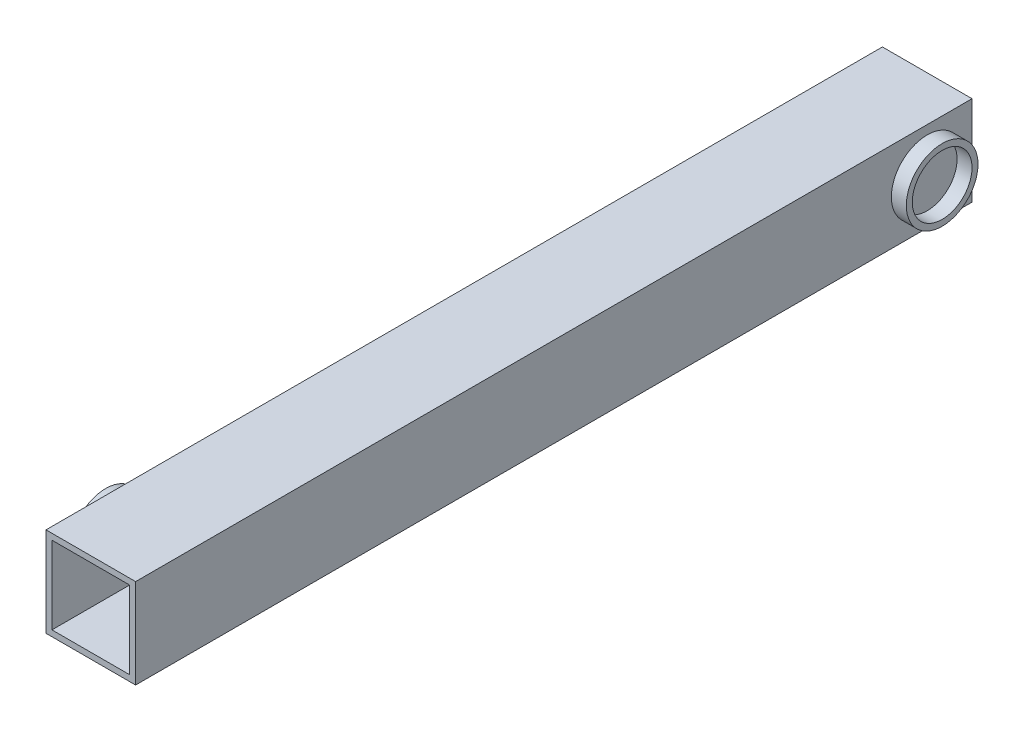
SolidWorks part; units mm, degrees
ref_plane "Front Plane" through (0, 0, 0) normal (0, 0, 1) x (1, 0, 0)
ref_plane "Top Plane" through (0, 0, 0) normal (0, 1, 0) x (1, 0, 0)
ref_plane "Right Plane" through (0, 0, 0) normal (1, 0, 0) x (0, 0, -1)
sketch "Sketch1" plane through (0, 0, 0) normal (0, 0, 1) x (1, 0, 0)
  line L0 (-13, 13) -> (-13, -13)
  line L1 (-15, 15) -> (15, 15)
  line L2 (-15, 15) -> (-15, -15)
  line L3 (-15, -15) -> (15, -15)
  line L4 (15, 15) -> (15, -15)
  line L5 (-15, 15) -> (15, -15) construction
  line L6 (-15, -15) -> (15, 15) construction
  line L7 (-13, -13) -> (13, -13)
  line L8 (13, 13) -> (13, -13)
  line L9 (-13, 13) -> (13, 13)
  point P0 (0, 0)
  dimension "D1" = 30
  dimension "D2" = 30
  dimension "D3" = 2
extrude "Boss-Extrude1" add sketch "Sketch1" along normal blind 280
sketch "Sketch2" plane through (15, 0, 0) normal (1, 0, 0) x (0, 0, -1)
  line L0 (-140, 15) -> (-140, -15) construction
  line L1 (-280, 15) -> (0, 15) construction
  line L2 (-280, -15) -> (0, -15) construction
  circle A0 centre (-15, 0) radius 12
  circle A1 centre (-15, 0) radius 10
  dimension "D1" = 24
  dimension "D3" = 15
  dimension "D2" = 2
extrude "Boss-Extrude2" add sketch "Sketch2" along normal blind 5
sketch "Sketch3" plane through (-15, 0, 0) normal (-1, 0, 0) x (0, 0, 1)
  circle A0 centre (255, 0) radius 10
  circle A3 centre (255, 0) radius 12
  dimension "D1" = 20
  dimension "D2" = 255
extrude "Boss-Extrude3" add sketch "Sketch3" along normal blind 5
